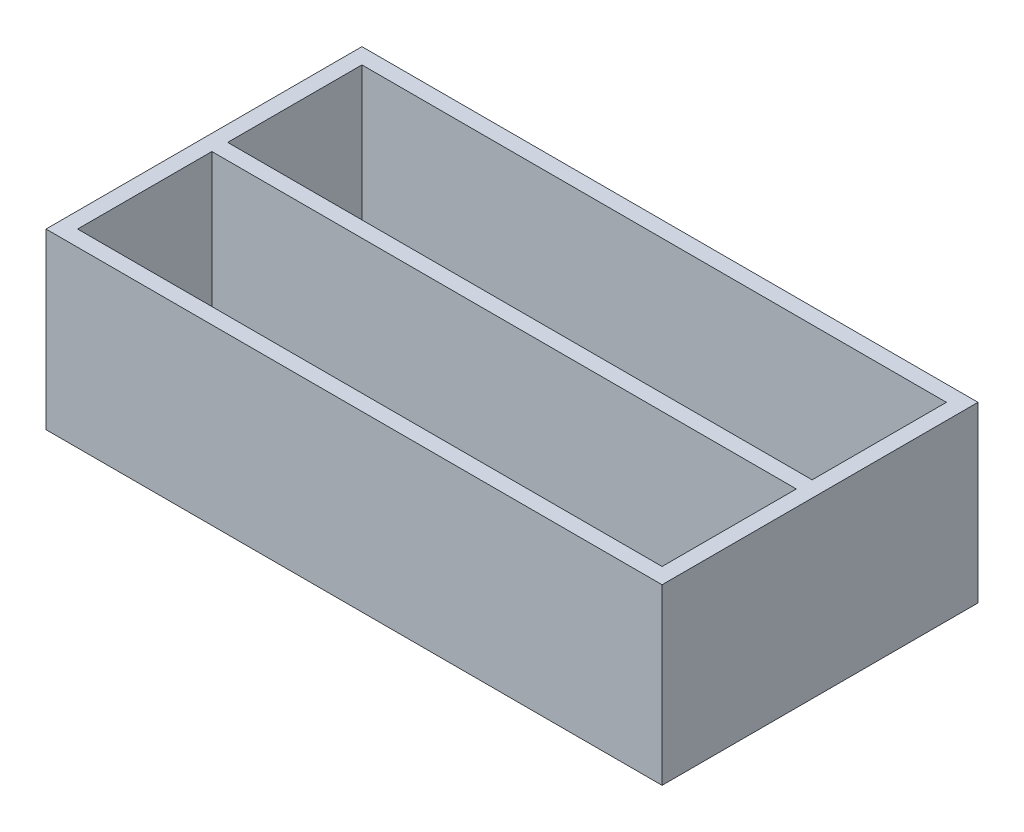
SolidWorks part; units mm, degrees
ref_plane "Front Plane" through (0, 0, 0) normal (0, 0, 1) x (1, 0, 0)
ref_plane "Top Plane" through (0, 0, 0) normal (0, 1, 0) x (1, 0, 0)
ref_plane "Right Plane" through (0, 0, 0) normal (1, 0, 0) x (0, 0, -1)
sketch "Sketch1" plane through (0, 0, 0) normal (0, 1, 0) x (1, 0, 0)
  line L1 (0, 0) -> (-78, 0)
  line L2 (0, 0) -> (0, 40)
  line L3 (0, 40) -> (-78, 40)
  line L4 (-78, 0) -> (-78, 40)
  dimension "D1" = 78
  dimension "D2" = 40
extrude "Boss-Extrude1" add sketch "Sketch1" along normal blind 22
sketch "Sketch2" plane through (0, 22, 0) normal (0, 1, 0) x (1, 0, 0)
  line L4 (-76, 21) -> (-2, 21)
  line L5 (-76, 20) -> (-2, 20) construction
  line L6 (-76, 19) -> (-2, 19)
  line L8 (-2, 2) -> (-2, 38)
  line L9 (-2, 38) -> (-76, 38)
  line L10 (-76, 38) -> (-76, 2)
  line L11 (-76, 2) -> (-2, 2)
  line L12 (-2, 2) -> (-2, 38)
  line L13 (-2, 38) -> (-76, 38)
  line L14 (-76, 38) -> (-76, 2)
  line L15 (-76, 2) -> (-2, 2)
  dimension "D2" = 1
  dimension "D3" = 1
  dimension "D1" = 2
extrude "Cut-Extrude1" cut sketch "Sketch2" against normal blind 20 contours L13 L14 L4 L12 | L14 L15 L12 L6
